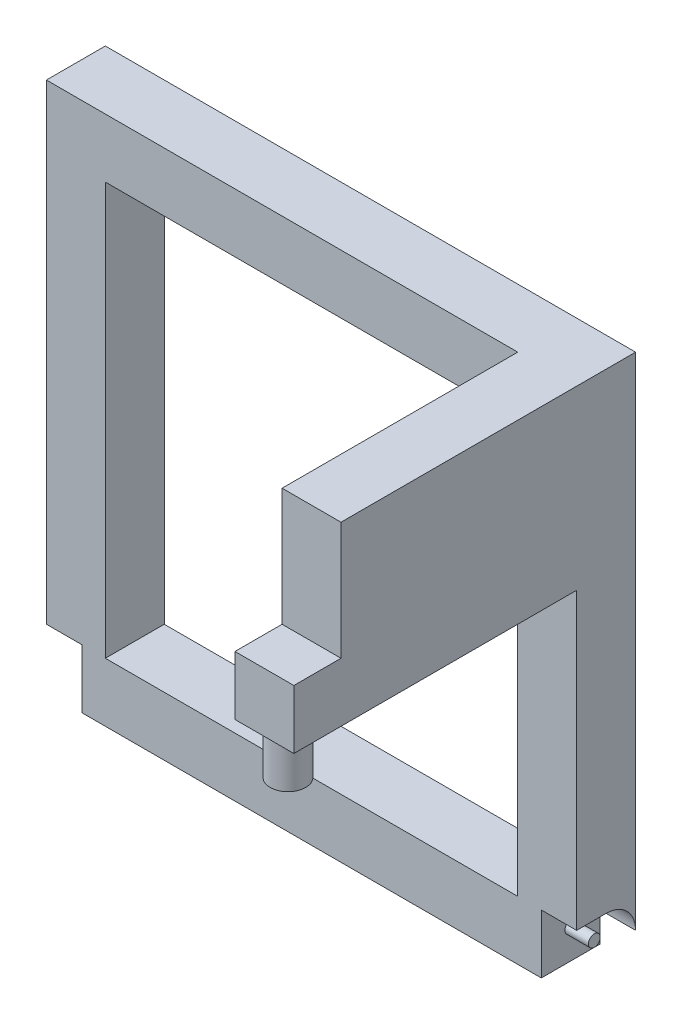
SolidWorks part; units mm, degrees
ref_plane "前基準面" through (0, 0, 0) normal (0, 0, 1) x (1, 0, 0)
ref_plane "上基準面" through (0, 0, 0) normal (0, 1, 0) x (1, 0, 0)
ref_plane "右基準面" through (0, 0, 0) normal (1, 0, 0) x (0, 0, -1)
sketch "草圖1" plane through (0, 0, 0) normal (0, 0, 1) x (1, 0, 0)
  line L0 (17.5, -17.5) -> (22.5, -22.5) construction
  line L1 (-22.5, 22.5) -> (22.5, 22.5)
  line L2 (-22.5, 22.5) -> (-22.5, -22.5)
  line L3 (-22.5, -22.5) -> (22.5, -22.5)
  line L4 (22.5, 22.5) -> (22.5, -22.5)
  line L5 (-22.5, 22.5) -> (-17.5, 17.5) construction
  line L6 (-22.5, -22.5) -> (-17.5, -17.5) construction
  line L7 (-17.5, 17.5) -> (17.5, 17.5)
  line L8 (-17.5, 17.5) -> (-17.5, -17.5)
  line L9 (-17.5, -17.5) -> (17.5, -17.5)
  line L10 (17.5, 17.5) -> (17.5, -17.5)
  line L13 (17.5, 17.5) -> (22.5, 22.5) construction
  point P0 (0, 0)
  point P5 (0, 0)
  dimension "D1" = 45
  dimension "D2" = 45
  dimension "D3" = 5
extrude "填料-伸長1" add sketch "草圖1" along normal blind 5
sketch "草圖2" plane through (-22.5, 0, 0) normal (-1, 0, 0) x (0, 0, 1)
  line L0 (5, -22.5) -> (0, -22.5) construction
  line L1 (0, 22.5) -> (0, -22.5) construction
  line L2 (5, 22.5) -> (5, -22.5) construction
  line L3 (2.5, -17.5) -> (5, -17.5)
  line L4 (0, -20) -> (0, -22.5)
  line L5 (0, -22.5) -> (5, -22.5)
  line L6 (5, -22.5) -> (5, -17.5)
  arc A0 (2.5, -17.5) -> (0, -20) centre (2.5, -20) ccw
extrude "除料-伸長1" cut sketch "草圖2" against normal blind 3
mirror "鏡射1" about plane through (0, 0, 0) normal (1, 0, 0) of "除料-伸長1"
sketch "草圖3" plane through (-19.5, 0, 0) normal (-1, 0, 0) x (0, 0, 1)
  circle A0 centre (2.5, -20) radius 0.5
  dimension "D1" = 1
extrude "填料-伸長2" add sketch "草圖3" along normal blind 2
mirror "鏡射2" about plane through (0, 0, 0) normal (1, 0, 0) of "填料-伸長2"
sketch "草圖4" plane through (0, 0, 5) normal (0, 0, 1) x (1, 0, 0)
  line L0 (17.5, -17.5) -> (17.5, 17.5) construction
  line L1 (22.5, 22.5) -> (17.5, 22.5)
  line L2 (22.5, 22.5) -> (22.5, 7.5)
  line L3 (22.5, 7.5) -> (17.5, 7.5)
  line L4 (17.5, 22.5) -> (17.5, 7.5)
  dimension "D1" = 15
extrude "填料-伸長3" add sketch "草圖4" along normal blind 20
sketch "草圖5" plane through (0, 0, 25) normal (0, 0, 1) x (1, 0, 0)
  line L0 (17.5, 22.5) -> (17.5, 7.5) construction
  line L1 (22.5, 7.5) -> (17.5, 7.5)
  line L2 (22.5, 7.5) -> (22.5, 12.5)
  line L3 (22.5, 12.5) -> (17.5, 12.5)
  line L4 (17.5, 7.5) -> (17.5, 12.5)
  dimension "D1" = 5
extrude "填料-伸長4" add sketch "草圖5" along normal blind 4
sketch "草圖6" plane through (0, 7.5, 0) normal (0, -1, 0) x (1, 0, 0)
  line L0 (17.5, 29) -> (22.5, 29) construction
  circle A0 centre (20, 27) radius 1.5
  point P2 (20, 29)
  dimension "D1" = 3
  dimension "D2" = 2
extrude "填料-伸長5" add sketch "草圖6" along normal blind 4
